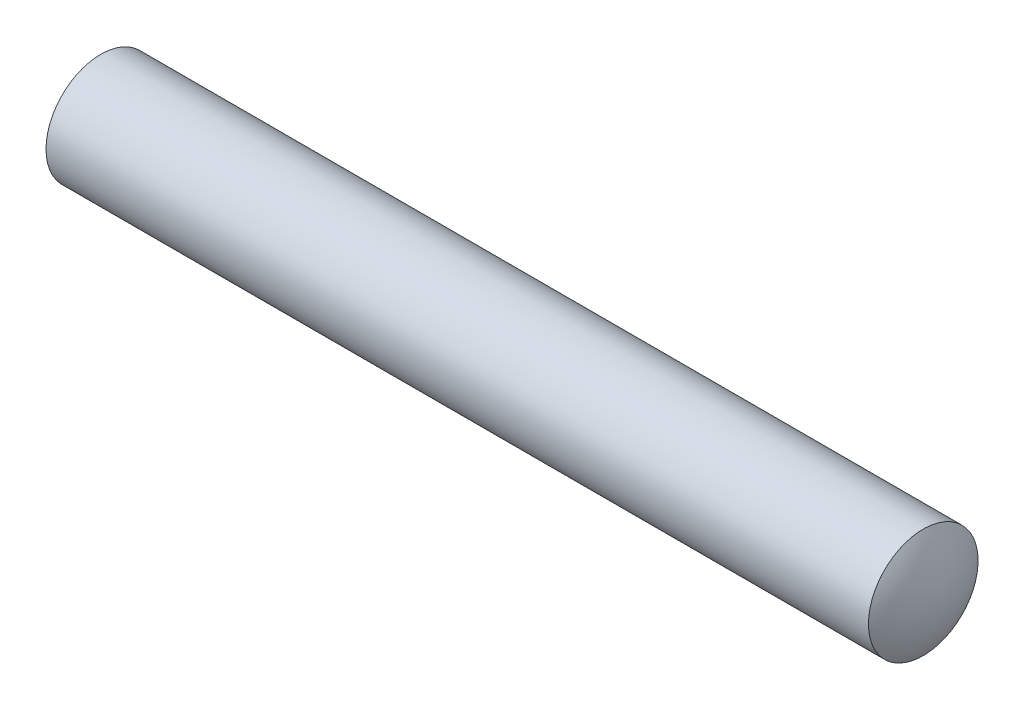
SolidWorks part; units mm, degrees
ref_plane "Спереди" through (0, 0, 0) normal (0, 0, 1) x (1, 0, 0)
ref_plane "Сверху" through (0, 0, 0) normal (0, 1, 0) x (1, 0, 0)
ref_plane "Справа" through (0, 0, 0) normal (1, 0, 0) x (0, 0, -1)
sketch "Эскиз1" plane through (0, 0, 0) normal (0, 0, 1) x (1, 0, 0)
  line L0 (0, 0) -> (14.3069, 0) construction
  line L1 (0, 0) -> (0, 6.3046) construction
  line L3 (0, 2) -> (30, 2)
  line L6 (30, 2) -> (30, -0.9836) construction
  line L7 (-0.6, 0) -> (30.6, 0)
  arc A1 (0, 2) -> (-0.6, 0) centre (3.3985, -0.1095) ccw
  arc A2 (30, 2) -> (30.6, 0) centre (26.6015, -0.1095) cw
  point P7 (0, 0)
  point P10 (0, 0)
  dimension "D1" = 0.6
  dimension "D4" = 4
  dimension "D6" = 4
  dimension "D2" = 4
  dimension "D3" = 30
  dimension "D5" = 0.6
revolve "Повернуть2" add sketch "Эскиз1" angle 360 about L0
